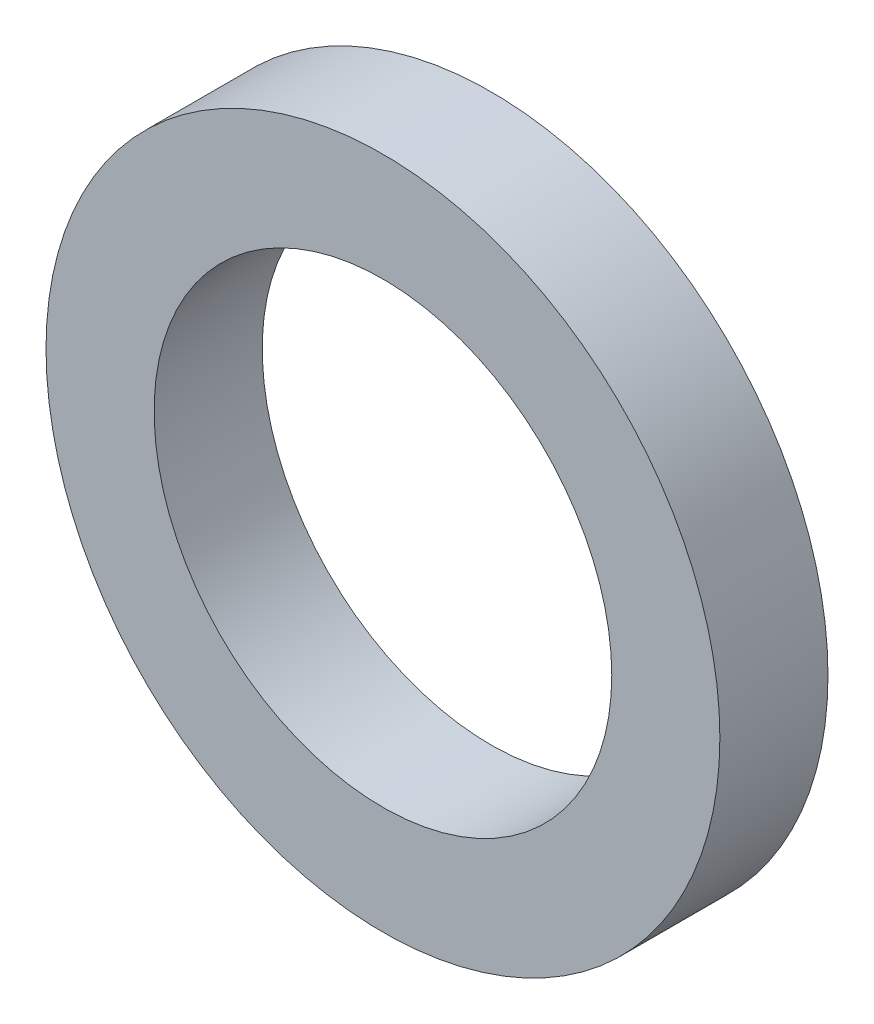
SolidWorks part; units mm, degrees
ref_plane "Front Plane" through (0, 0, 0) normal (0, 0, 1) x (1, 0, 0)
ref_plane "Top Plane" through (0, 0, 0) normal (0, 1, 0) x (1, 0, 0)
ref_plane "Right Plane" through (0, 0, 0) normal (1, 0, 0) x (0, 0, -1)
sketch "Sketch1" plane through (0, 0, 0) normal (0, 0, 1) x (1, 0, 0)
  circle A0 centre (0, 0) radius 6.35
  circle A1 centre (0, 0) radius 9.35
  dimension "D1" = 12.7
  dimension "D2" = 3
extrude "Boss-Extrude1" add sketch "Sketch1" along normal blind 3
